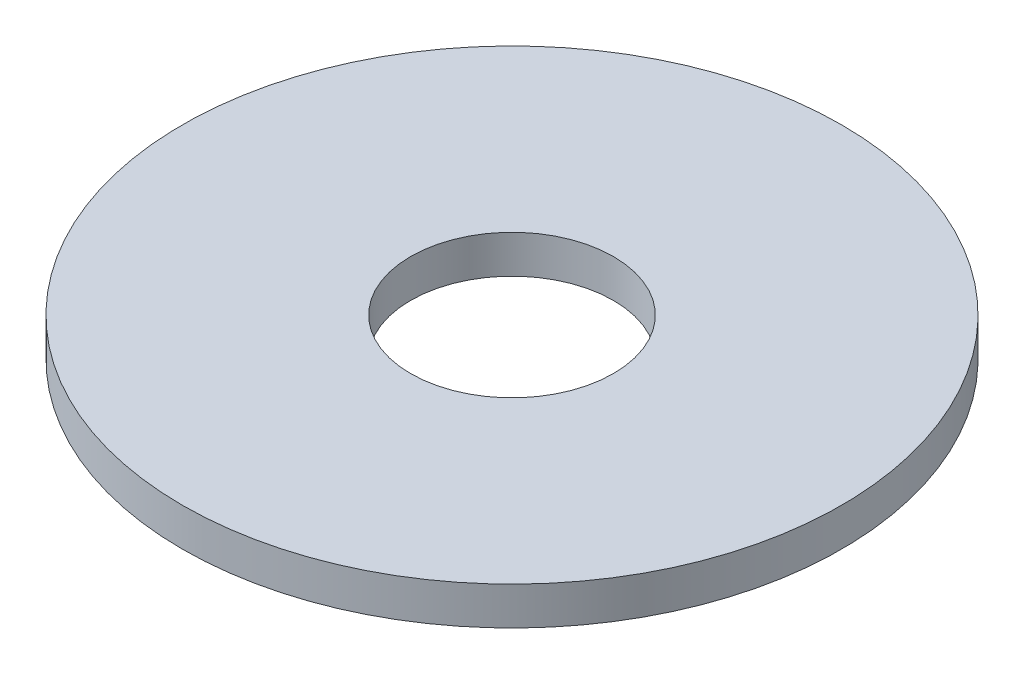
SolidWorks part; units mm, degrees
material "ABS PC"
ref_plane "Front Plane" through (0, 0, 0) normal (0, 0, 1) x (1, 0, 0)
ref_plane "Top Plane" through (0, 0, 0) normal (0, 1, 0) x (1, 0, 0)
ref_plane "Right Plane" through (0, 0, 0) normal (1, 0, 0) x (0, 0, -1)
sketch "Sketch1" plane through (0, 0, 0) normal (0, 1, 0) x (1, 0, 0)
  circle A0 centre (0, 0) radius 13
  circle A1 centre (0, 0) radius 4
  dimension "D1" = 26
  dimension "D2" = 8
extrude "Boss-Extrude1" add sketch "Sketch1" along normal blind 1.5
